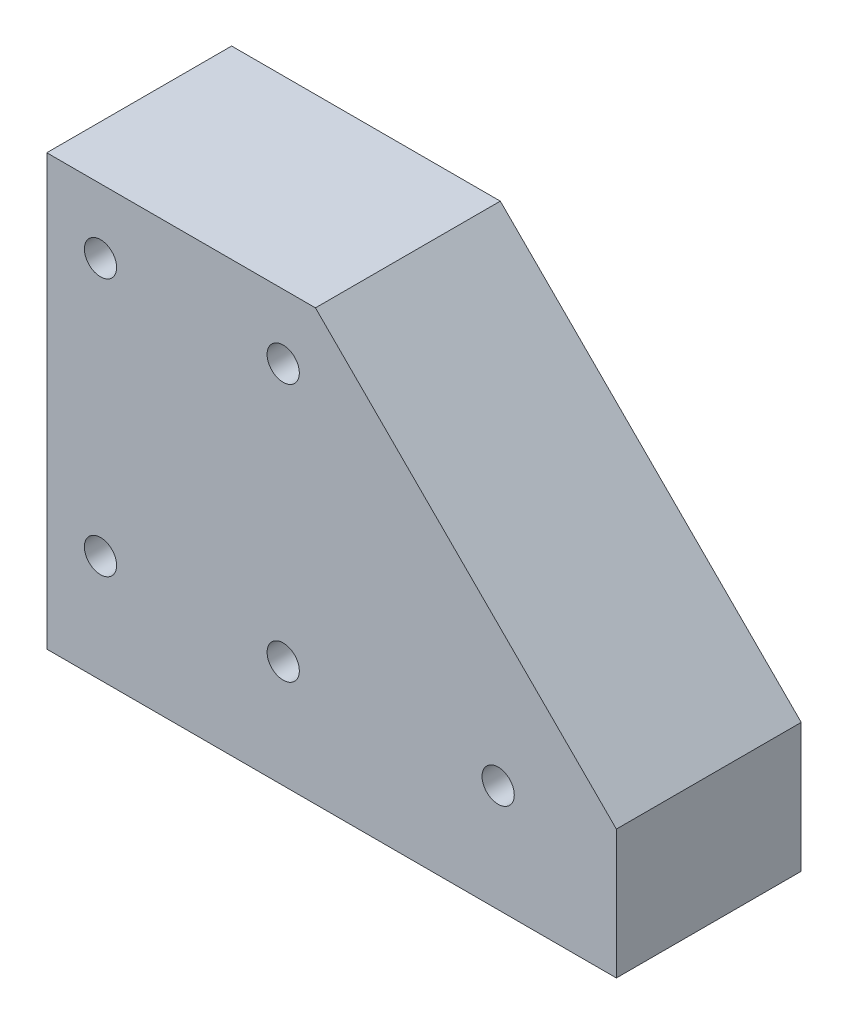
SolidWorks part; units mm, degrees
ref_plane "前视基准面" through (0, 0, 0) normal (0, 0, 1) x (1, 0, 0)
ref_plane "上视基准面" through (0, 0, 0) normal (0, 1, 0) x (1, 0, 0)
ref_plane "右视基准面" through (0, 0, 0) normal (1, 0, 0) x (0, 0, -1)
other "Configuration Table"
sketch "草图1" plane through (0, 0, 0) normal (0, 0, 1) x (1, 0, 0)
  line L1 (0, 0) -> (53, 0)
  line L2 (0, 0) -> (0, 40)
  line L3 (0, 40) -> (53, 40)
  line L4 (53, 0) -> (53, 40)
  dimension "D1" = 53
  dimension "D2" = 40
extrude "凸台-拉伸1" add sketch "草图1" along normal blind 17.2
sketch "草图2" plane through (0, 0, 17.2) normal (0, 0, 1) x (1, 0, 0)
  line L5 (25, 40) -> (53, 40)
  line L6 (53, 40) -> (0, 40) construction
  line L7 (53, 40) -> (53, 12)
  line L8 (53, 0) -> (53, 40) construction
  line L9 (53, 12) -> (25, 40)
  dimension "D1" = 28
  dimension "D2" = 28
extrude "切除-拉伸1" cut sketch "草图2" against normal through all
sketch "草图3" plane through (0, 0, 17.2) normal (0, 0, 1) x (1, 0, 0)
  line L1 (0, 40) -> (0, 0) construction
  line L2 (0, 0) -> (53, 0) construction
  circle A0 centre (5, 34) radius 1.5
  circle A1 centre (5, 10) radius 1.5
  circle A2 centre (22, 34) radius 1.5
  circle A3 centre (22, 10) radius 1.5
  circle A4 centre (42, 10) radius 1.5
  dimension "D1" = 3
  dimension "D2" = 10
  dimension "D3" = 5
  dimension "D4" = 17
  dimension "D5" = 24
  dimension "D6" = 20
extrude "切除-拉伸2" cut sketch "草图3" against normal through all
